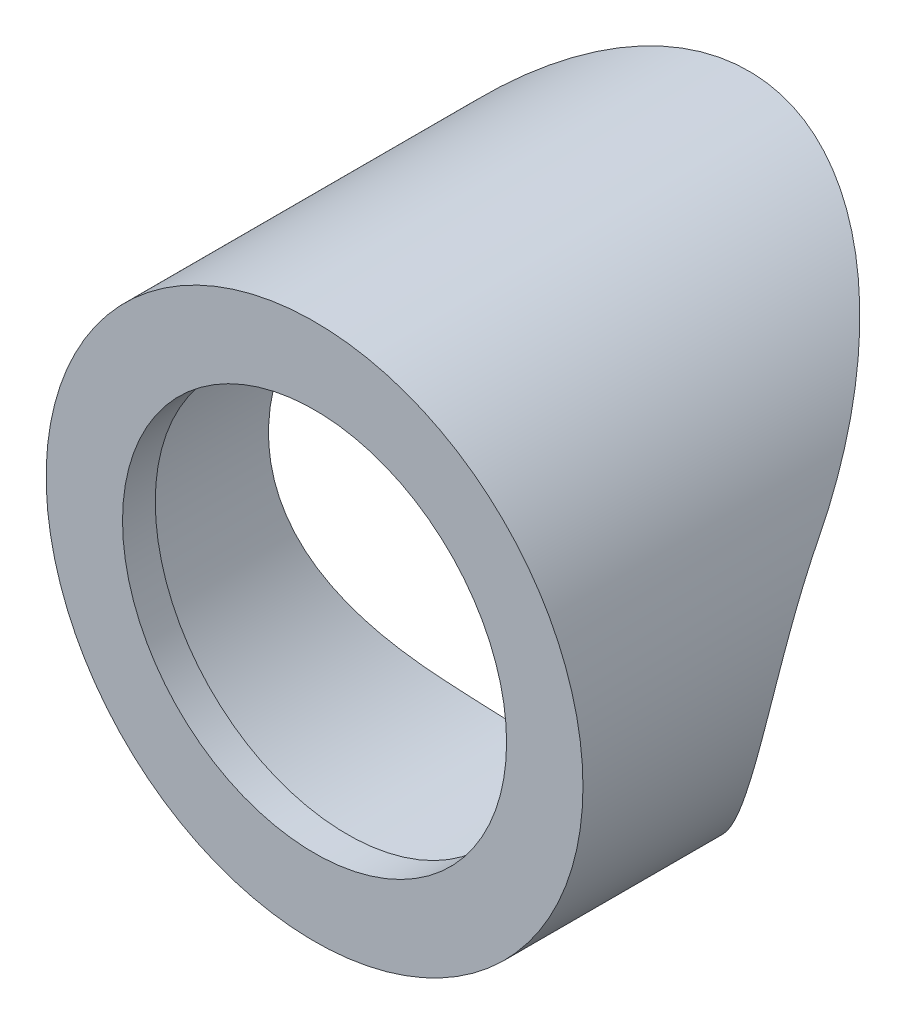
SolidWorks part; units mm, degrees
ref_plane "Front Plane" through (0, 0, 0) normal (0, 0, 1) x (1, 0, 0)
ref_plane "Top Plane" through (0, 0, 0) normal (0, 1, 0) x (1, 0, 0)
ref_plane "Right Plane" through (0, 0, 0) normal (1, 0, 0) x (0, 0, -1)
sketch "Esquisse2" plane through (0, 0, 0) normal (1, 0, 0) x (0, 0, -1)
  line L0 (0, 0) -> (15, 0) construction
  line L1 (0, 8.8) -> (1.5, 8.8)
  line L2 (0, 8.8) -> (0, 12.3)
  line L3 (0, 12.3) -> (20, 12.3)
  line L4 (20, 10.8) -> (20, 12.3)
  line L7 (20, 10.8) -> (1.5, 10.8)
  line L8 (1.5, 8.8) -> (1.5, 10.8)
  dimension "D1" = 1.5
  dimension "D2" = 20
  dimension "D3" = 21.6
  dimension "D4" = 2
  dimension "D5" = 1.5
revolve "Révolution1" add sketch "Esquisse2" angle 360 about L0
sketch "Esquisse3" plane through (0, 0, 0) normal (1, 0, 0) x (0, 0, -1)
  line L5 (20, 12.3) -> (0, 12.3) construction
  line L6 (0, -12.3) -> (20, -12.3) construction
  line L7 (12.9, -12.3) -> (20, -12.3)
  line L8 (20, -12.3) -> (20, 12.3)
  line L9 (20, 12.3) -> (19.9, 12.3)
  line L10 (11.3604, 3.7786) -> (19.9, 12.3)
  line L11 (20, 12.3) -> (0, 12.3) construction
  line L12 (10.7318, -9.6899) -> (12.9, -12.3)
  arc A1 (11.3604, 3.7786) -> (10.7318, -9.6899) centre (18.4239, -3.3) ccw
  dimension "D1" = 10
  dimension "D2" = 9
  dimension "D3" = 0.1
  dimension "D4" = 7.1
extrude "Enlèv. mat.-Extru.1" cut sketch "Esquisse3" against normal through all both and the other way through all
sketch "Esquisse4" plane through (0, 0, -1.5) normal (0, 0, -1) x (-1, 0, 0)
  line L1 (1, 9.3) -> (-1, 9.3)
  line L2 (1, 9.3) -> (1, 10.8)
  line L3 (1, 10.8) -> (-1, 10.8)
  line L4 (-1, 9.3) -> (-1, 10.8)
  line L5 (1, 9.3) -> (-1, 10.8) construction
  line L6 (1, 10.8) -> (-1, 9.3) construction
  arc A0 (10.1174, 3.7786) -> (-10.1174, 3.7786) centre (0, 0) ccw construction
  point P0 (0, 10.05)
  dimension "D1" = 2
  dimension "D2" = 1.5
extrude "Boss.-Extru.1" add sketch "Esquisse4" along normal blind 5
